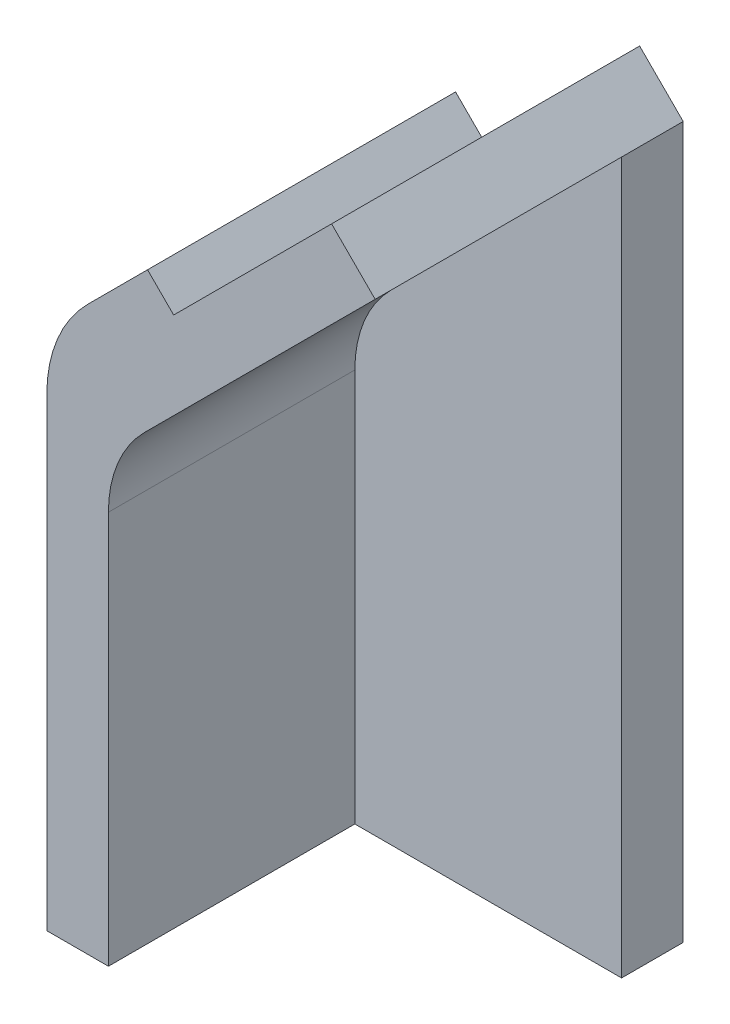
SolidWorks part; units mm, degrees
ref_plane "Front Plane" through (0, 0, 0) normal (0, 0, 1) x (1, 0, 0)
ref_plane "Top Plane" through (0, 0, 0) normal (0, 1, 0) x (1, 0, 0)
ref_plane "Right Plane" through (0, 0, 0) normal (1, 0, 0) x (0, 0, -1)
sketch "Sketch1" plane through (-44.3957, 24.7263, -28.895) normal (0, 0, 1) x (0.7071, -0.7071, 0)
  line L0 (4.8, 0) -> (3.5964, 0) construction
  line L1 (4.8, 7) -> (4.8, 0) construction
  line L2 (4.8, 0) -> (3.6, 0)
  line L3 (4.8, 7) -> (4.8, 0)
  line L4 (15.6568, -17.0347) -> (4.9986, -6.3764) construction
  line L5 (3.6, -3) -> (3.6, 0) construction
  line L6 (15.6568, -17.0347) -> (4.9986, -6.3764)
  line L7 (3.6, -3) -> (3.6, 0)
  arc A0 (3.6, -3) -> (4.9986, -6.3764) centre (8.375, -3) ccw construction
  arc A1 (3.6, -3) -> (4.9986, -6.3764) centre (8.375, -3) ccw
sketch "Sketch2" plane through (-44.3957, 24.7263, -28.895) normal (0, 0, 1) x (0.7071, -0.7071, 0)
  line L8 (5.05, 7) -> (7.05, 7)
  line L9 (7.05, 7) -> (7.05, -3.589)
  line L10 (8.2216, -6.4175) -> (17.2478, -15.4437)
  line L11 (17.2478, -15.4437) -> (15.8336, -16.8579)
  line L38 (5.05, -0.25) -> (5.05, 7)
  line L39 (3.85, -0.25) -> (5.05, -0.25)
  line L40 (3.85, -3) -> (3.85, -0.25)
  line L41 (15.8336, -16.8579) -> (5.1753, -6.1997)
  line L42 (5.05, -0.25) -> (5.05, 7)
  line L43 (3.85, -0.25) -> (5.05, -0.25)
  line L44 (3.85, -3) -> (3.85, -0.25)
  line L45 (15.8336, -16.8579) -> (5.1753, -6.1997)
  arc A2 (7.05, -3.589) -> (8.2216, -6.4175) centre (11.05, -3.589) ccw
  arc A12 (3.85, -3) -> (5.1753, -6.1997) centre (8.375, -3) ccw
  arc A13 (3.85, -3) -> (5.1753, -6.1997) centre (8.375, -3) ccw
  point P0 (7.05, -3.7398)
  point P1 (5.05, 7.0216)
  point P2 (15.9511, -16.8579)
  point P12 (16.8615, -15.6141)
  point P14 (6.2038, 7)
  point P15 (8.6146, -6.9797)
  dimension "D1" = 2
  dimension "D3" = 4
  dimension "D2" = 0.25
extrude "Boss-Extrude1" add sketch "Sketch2" along normal mid plane 10
sketch "Sketch3" plane through (0, 0, -33.895) normal (0, 0, -1) x (-1, 0, 0)
  line L0 (34.4608, 24.691) -> (34.4608, 1.61)
  line L1 (34.4608, 1.61) -> (43.12, 1.61)
  line L2 (41.9484, 17.2034) -> (34.4608, 24.691) construction
  line L3 (43.12, 1.61) -> (43.12, 14.375) construction
  line L4 (41.9484, 17.2034) -> (34.4608, 24.691)
  line L5 (43.12, 1.61) -> (43.12, 14.375)
  arc A0 (43.12, 14.375) -> (41.9484, 17.2034) centre (39.12, 14.375) ccw construction
  arc A1 (43.12, 14.375) -> (41.9484, 17.2034) centre (39.12, 14.375) ccw
extrude "Boss-Extrude2" add sketch "Sketch3" against normal blind 2
